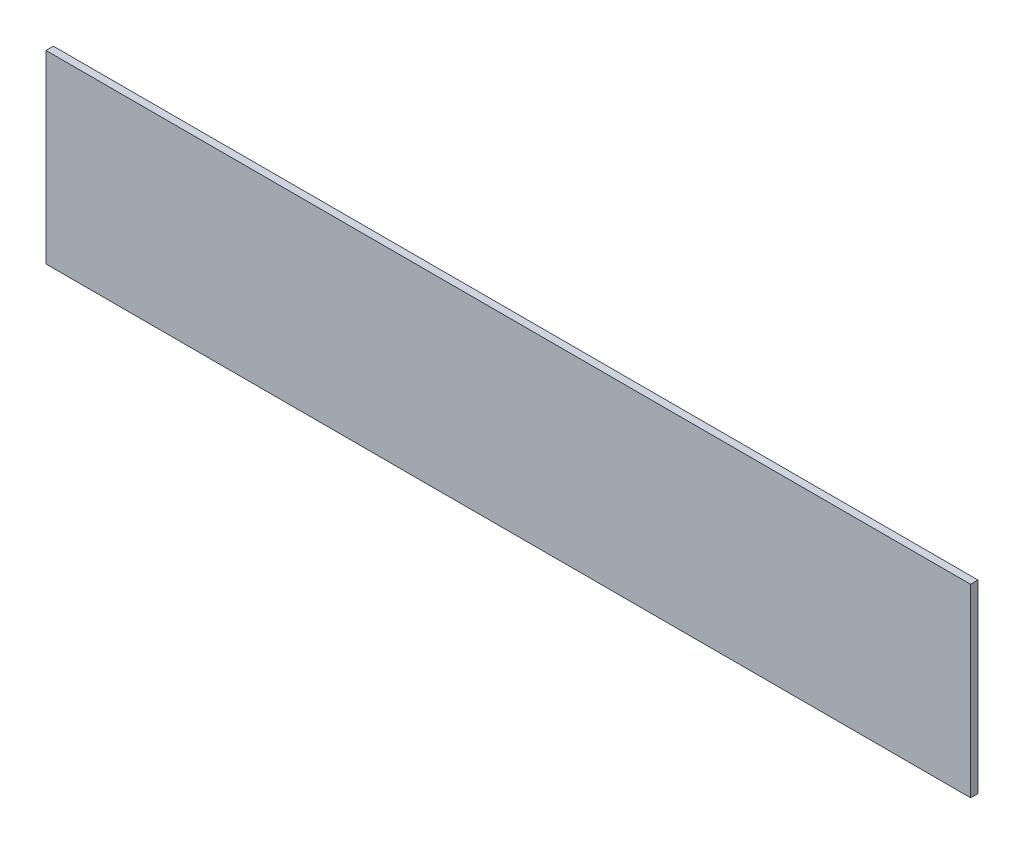
SolidWorks part; units mm, degrees
ref_plane "Plano frontal" through (0, 0, 0) normal (0, 0, 1) x (1, 0, 0)
ref_plane "Plano superior" through (0, 0, 0) normal (0, 1, 0) x (1, 0, 0)
ref_plane "Plano direito" through (0, 0, 0) normal (1, 0, 0) x (0, 0, -1)
sketch "Esboço1" plane through (0, 0, 0) normal (0, 0, 1) x (1, 0, 0)
  line L1 (-12.5, -2.5) -> (12.5, -2.5)
  line L2 (-12.5, -2.5) -> (-12.5, 2.5)
  line L3 (-12.5, 2.5) -> (12.5, 2.5)
  line L4 (12.5, -2.5) -> (12.5, 2.5)
  line L5 (-12.5, -2.5) -> (12.5, 2.5) construction
  line L6 (-12.5, 2.5) -> (12.5, -2.5) construction
  point P0 (0, 0)
  dimension "D1" = 25
  dimension "D2" = 5
extrude "Ressalto-extrusão1" add sketch "Esboço1" along normal blind 0.2
